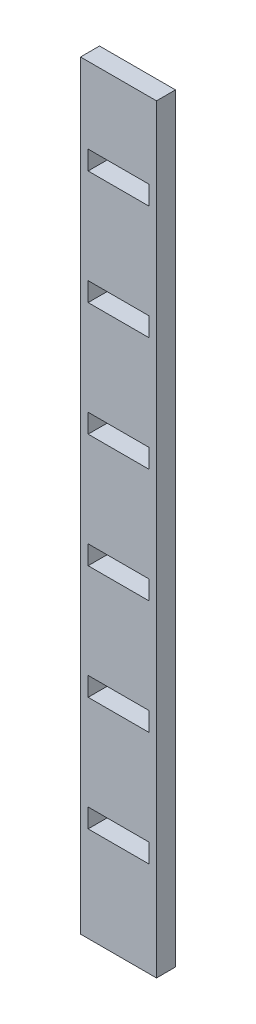
SolidWorks part; units mm, degrees
ref_plane "前视基准面" through (0, 0, 0) normal (0, 0, 1) x (1, 0, 0)
ref_plane "上视基准面" through (0, 0, 0) normal (0, 1, 0) x (1, 0, 0)
ref_plane "右视基准面" through (0, 0, 0) normal (1, 0, 0) x (0, 0, -1)
other "Configuration Table"
sketch "草图1" plane through (0, 0, 0) normal (0, 0, 1) x (1, 0, 0)
  line L0 (-100, 0) -> (-100, 2000)
  line L1 (-100, 2000) -> (100, 2000)
  line L2 (100, 2000) -> (100, 0)
  line L3 (100, 0) -> (-100, 0)
  line L4 (-80, 300) -> (80, 300)
  line L5 (80, 300) -> (80, 250)
  line L6 (80, 250) -> (-80, 250)
  line L7 (-80, 250) -> (-80, 300)
  line L8 (-80, 600) -> (80, 600)
  line L9 (80, 600) -> (80, 550)
  line L10 (80, 550) -> (-80, 550)
  line L11 (-80, 550) -> (-80, 600)
  line L12 (-80, 900) -> (80, 900)
  line L13 (80, 900) -> (80, 850)
  line L14 (80, 850) -> (-80, 850)
  line L15 (-80, 850) -> (-80, 900)
  line L16 (-80, 1200) -> (80, 1200)
  line L17 (80, 1200) -> (80, 1150)
  line L18 (80, 1150) -> (-80, 1150)
  line L19 (-80, 1150) -> (-80, 1200)
  line L20 (-80, 1500) -> (80, 1500)
  line L21 (80, 1500) -> (80, 1450)
  line L22 (80, 1450) -> (-80, 1450)
  line L23 (-80, 1450) -> (-80, 1500)
  line L24 (-80, 1800) -> (80, 1800)
  line L25 (80, 1800) -> (80, 1750)
  line L26 (80, 1750) -> (-80, 1750)
  line L27 (-80, 1750) -> (-80, 1800)
extrude "凸台-拉伸1" add sketch "草图1" along normal blind 50
